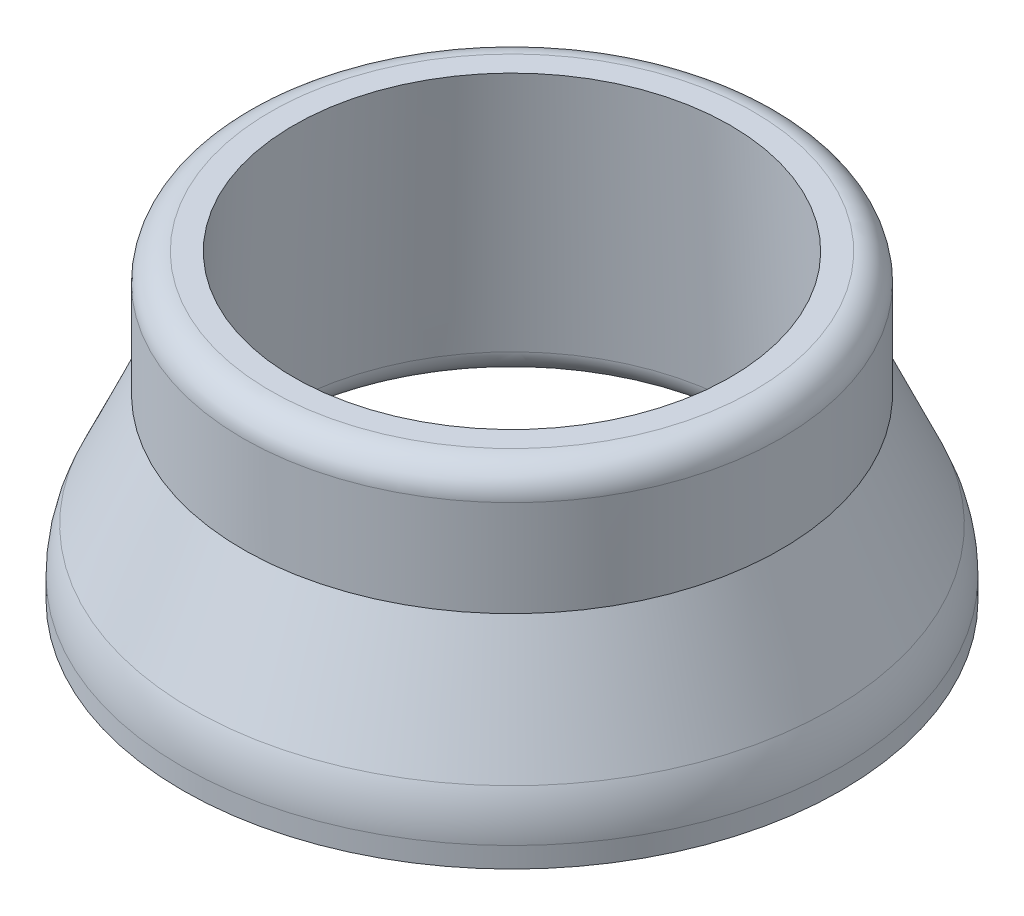
SolidWorks part; units mm, degrees
ref_plane "Front Plane" through (0, 0, 0) normal (0, 0, 1) x (1, 0, 0)
ref_plane "Top Plane" through (0, 0, 0) normal (0, 1, 0) x (1, 0, 0)
ref_plane "Right Plane" through (0, 0, 0) normal (1, 0, 0) x (0, 0, -1)
sketch "Sketch2" plane through (0, 0, 0) normal (0, 0, 1) x (1, 0, 0)
  line L0 (0, 0) -> (12, 0)
  line L1 (12, 1.6) -> (9.8, 6.5)
  line L2 (9.8, 6.5) -> (9.8, 11)
  line L3 (9.8, 11) -> (0, 11)
  line L4 (0, 11) -> (0, 0)
  line L5 (12, 1.6) -> (12, 0)
  dimension "D1" = 12
  dimension "D2" = 1.6
  dimension "D3" = 6.5
  dimension "D4" = 11
  dimension "D5" = 9.8
revolve "Revolve1" add sketch "Sketch2" angle 360 about L4
sketch "Sketch4" plane through (0, 0, 0) normal (0, 0, 1) x (1, 0, 0)
  line L0 (0, 0) -> (0, 11)
  line L1 (9.8, 11) -> (-9.8, 11) construction
  line L2 (0, 11) -> (7.95, 11)
  line L5 (12, 0) -> (0, 0)
  line L6 (7.95, 11) -> (8.45, 1.2)
  line L7 (-12, 0) -> (12, 0) construction
  line L8 (8.45, 1.2) -> (12, 0)
  point P6 (0, 0)
  dimension "D1" = 8.45
  dimension "D2" = 7.95
  dimension "D3" = 1.2
revolve "Cut-Revolve1" cut sketch "Sketch4" angle 360 about L0
fillet "Fillet1" radius 1 1 edges at (-9.8, 11, 0)
fillet "Fillet2" radius 1 1 edges at (0, 1.2, -8.45)
fillet "Fillet3" radius 4 1 edges at (-12, 1.6, 0)
